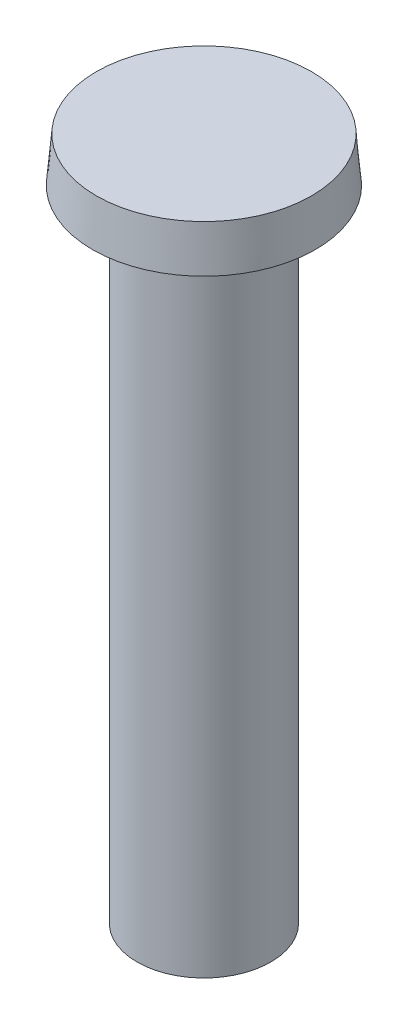
SolidWorks part; units mm, degrees
ref_plane "Front Plane" through (0, 0, 0) normal (0, 0, 1) x (1, 0, 0)
ref_plane "Top Plane" through (0, 0, 0) normal (0, 1, 0) x (1, 0, 0)
ref_plane "Right Plane" through (0, 0, 0) normal (1, 0, 0) x (0, 0, -1)
sketch "Sketch1" plane through (0, 0, 0) normal (0, 1, 0) x (1, 0, 0)
  circle A0 centre (0, 0) radius 2.25
  dimension "D1" = 4.5
extrude "Boss-Extrude1" add sketch "Sketch1" along normal blind 21.5
sketch "Sketch2" plane through (0, 21.5, 0) normal (0, 1, 0) x (1, 0, 0)
  circle A0 centre (0, 0) radius 3.75
  circle A1 centre (0, 0) radius 2.25 construction
  dimension "D1" = 1.5
extrude "Boss-Extrude2" add sketch "Sketch2" along normal blind 1.5 draft 5
sketch "Sketch3" plane through (0, 0, 0) normal (0, -1, 0) x (1, 0, 0)
  circle A0 centre (0, 0) radius 1
  dimension "D1" = 2
extrude "Cut-Extrude1" cut sketch "Sketch3" against normal blind 6 draft 1
